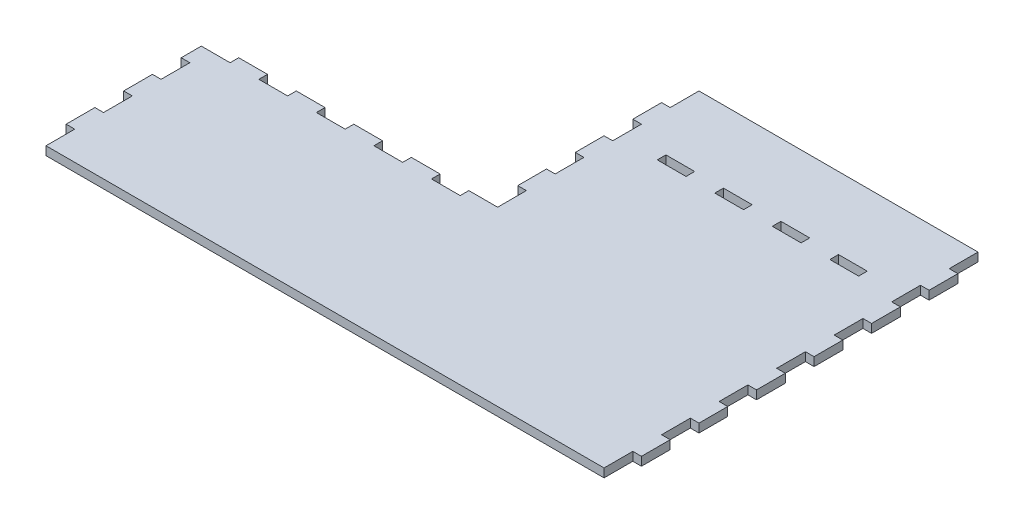
SolidWorks part; units mm, degrees
ref_plane "Front Plane" through (0, 0, 0) normal (0, 0, 1) x (1, 0, 0)
ref_plane "Top Plane" through (0, 0, 0) normal (0, 1, 0) x (1, 0, 0)
ref_plane "Right Plane" through (0, 0, 0) normal (1, 0, 0) x (0, 0, -1)
sketch "Sketch1" plane through (0, 0, 0) normal (0, 1, 0) x (1, 0, 0)
  line L1 (-100, -65) -> (100, -65)
  line L2 (-100, -65) -> (-100, 65)
  line L3 (-100, 65) -> (100, 65)
  line L4 (100, -65) -> (100, 65)
  line L5 (-100, -65) -> (100, 65) construction
  line L6 (-100, 65) -> (100, -65) construction
  point P0 (0, 0)
  dimension "D1" = 200
  dimension "D2" = 130
extrude "Boss-Extrude1" add sketch "Sketch1" along normal blind 3
sketch "Sketch2" plane through (0, 3, 0) normal (0, 1, 0) x (1, 0, 0)
  line L1 (-100, 65) -> (-3, 65)
  line L2 (-100, 65) -> (-100, -5)
  line L3 (-100, -5) -> (-3, -5)
  line L4 (-3, 65) -> (-3, -5)
  dimension "D1" = 97
  dimension "D2" = 70
extrude "Cut-Extrude1" cut sketch "Sketch2" against normal through all
sketch "Sketch3" plane through (0, 3, 0) normal (0, 1, 0) x (1, 0, 0)
  line L1 (-100, -65) -> (-97, -65)
  line L2 (-100, -65) -> (-100, -55)
  line L3 (-100, -55) -> (-97, -55)
  line L4 (-97, -65) -> (-97, -55)
  dimension "D1" = 3
  dimension "D2" = 10
extrude "Cut-Extrude2" cut sketch "Sketch3" against normal through all
pattern_linear "LPattern1" count 3 spacing 20 along (0, 0, -1) of "Cut-Extrude2"
sketch "Sketch4" plane through (0, 3, 0) normal (0, 1, 0) x (1, 0, 0)
  line L1 (100, -65) -> (97, -65)
  line L2 (100, -65) -> (100, -55)
  line L3 (100, -55) -> (97, -55)
  line L4 (97, -65) -> (97, -55)
  dimension "D1" = 3
  dimension "D2" = 10
extrude "Cut-Extrude3" cut sketch "Sketch4" against normal through all
pattern_linear "LPattern2" count 7 spacing 20 along (0, 0, -1) of "Cut-Extrude3"
sketch "Sketch5" plane through (0, 3, 0) normal (0, 1, 0) x (1, 0, 0)
  line L1 (-3, 65) -> (0, 65)
  line L2 (-3, 65) -> (-3, 55)
  line L3 (-3, 55) -> (0, 55)
  line L4 (0, 65) -> (0, 55)
  dimension "D1" = 10
  dimension "D2" = 3
extrude "Cut-Extrude4" cut sketch "Sketch5" against normal through all
pattern_linear "LPattern3" count 4 spacing 20 along (0, 0, 1) of "Cut-Extrude4"
sketch "Sketch7" plane through (0, 3, 0) normal (0, 1, 0) x (1, 0, 0)
  line L1 (-100, -5) -> (0, -5) construction
  line L2 (-10, -5) -> (-20, -5)
  line L3 (-10, -5) -> (-10, -8)
  line L4 (-10, -8) -> (-20, -8)
  line L6 (-20, -5) -> (-20, -8)
  line L7 (0, -5) -> (0, 5) construction
  dimension "D1" = 10
  dimension "D2" = 3
  dimension "D3" = 10
extrude "Cut-Extrude7" cut sketch "Sketch7" against normal through all
pattern_linear "LPattern6" count 5 spacing 20 along (-1, 0, 0) of "Cut-Extrude7"
sketch "Sketch8" plane through (0, 3, 0) normal (0, 1, 0) x (1, 0, 0)
  line L0 (97, 65) -> (0, 65) construction
  line L1 (73.5, 40) -> (83.5, 40)
  line L2 (73.5, 40) -> (73.5, 37)
  line L3 (73.5, 37) -> (83.5, 37)
  line L4 (83.5, 40) -> (83.5, 37)
  line L5 (100, 45) -> (100, 55) construction
  dimension "D1" = 10
  dimension "D2" = 3
  dimension "D3" = 25
  dimension "D4" = 16.5
extrude "Cut-Extrude8" cut sketch "Sketch8" against normal through all
pattern_linear "LPattern8" count 4 spacing 20 along (-1, 0, 0) of "Cut-Extrude8"
